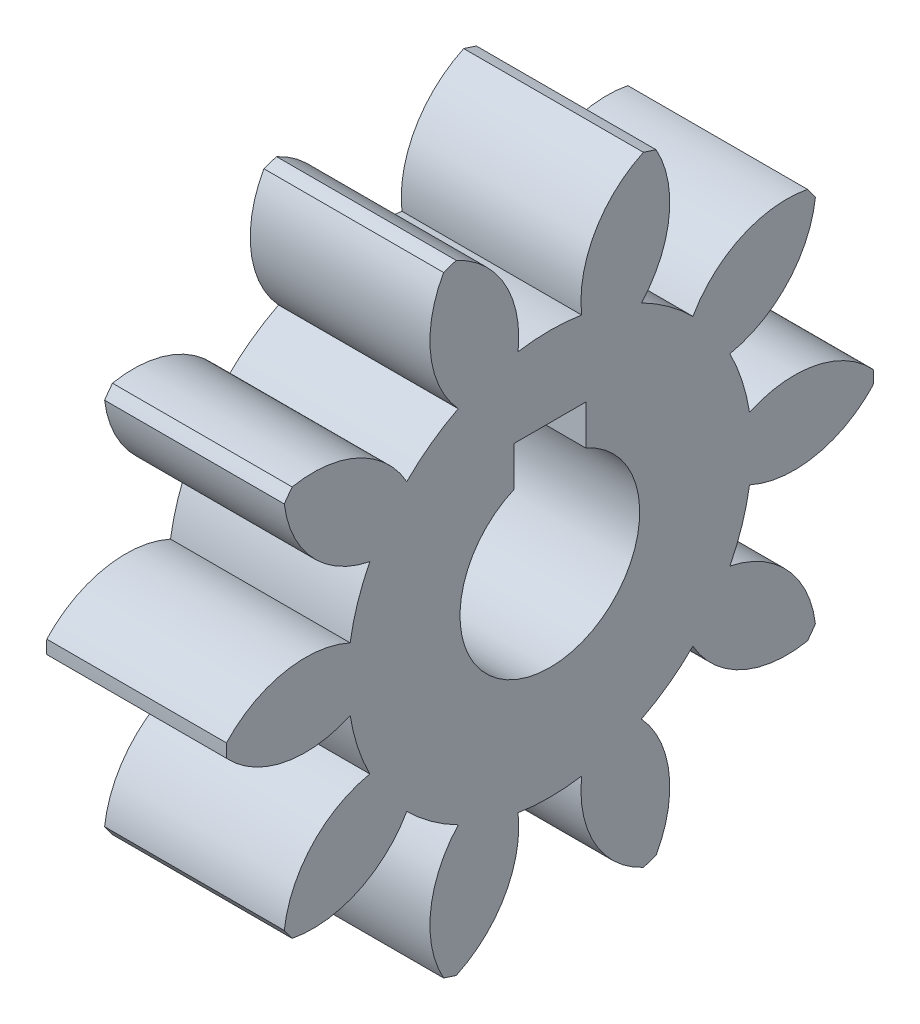
SolidWorks part; units mm, degrees
ref_plane "Plane1" through (0, 0, 0) normal (0, 0, 1) x (1, 0, 0)
ref_plane "Plane2" through (0, 0, 0) normal (0, 1, 0) x (1, 0, 0)
ref_plane "Plane3" through (0, 0, 0) normal (1, 0, 0) x (0, 0, -1)
sketch "HoldingSke" plane through (0, 0, 0) normal (0, 1, 0) x (1, 0, 0)
  line L0 (0, 0) -> (0.3283, -0.0579)
  line L1 (-15, 0) -> (100, 0) construction
  line L2 (0, 0) -> (-2.1039, 2.3779)
  line L3 (0, 0) -> (-11.863, 4.5341)
  line L4 (0, 0) -> (8.5048, 1.4996)
  line L5 (0, 0) -> (-46.8476, -17.4728)
  line L6 (0, 0) -> (-8.2896, -5.593)
  line L7 (-2.1039, 2.3779) -> (8.6586, 51.2059)
  line L8 (-76.2, 54.61) -> (-74.4, 54.61)
  line L9 (-71.009, 38.7566) -> (-53.1078, 45.2721)
  line L10 (-76.2, 71.12) -> (104.1128, 71.12)
  line L11 (0, 0) -> (-10, 0)
  line L12 (-76.2, 101.6) -> (-76.093, 101.6)
  line L13 (24.9733, 27.94) -> (52.9518, 28.4284)
  line L14 (24.9733, 27.94) -> (24.9743, 27.94)
  line L15 (24.9733, 27.94) -> (100.4006, 29.5858)
  line L16 (-63.627, -3) -> (-12.827, -3)
  circle A0 centre (0, 0) radius 5
  circle A1 centre (0, 0) radius 11.249
  circle A2 centre (0, 0) radius 37.5
  circle A3 centre (0, 0) radius 5
  dimension "MHD" = 22.498
  dimension "Hub_dia" = 75
  dimension "Bore" = 10
  dimension "MBD" = 10
  dimension "Num_teeth" = 10
  dimension "Pitch" = 0.3333
  dimension "Overall_len" = 50
  dimension "Show_teeth" = 10
  dimension "Thickness" = 10
  dimension "OAL" = 50.0001
  dimension "T_dim" = 1.8
  dimension "Ap" = 20
  dimension "H" = 19.05
  dimension "Pitch_radius" = 180.3128
  dimension "Width" = 10
  dimension "Backlash" = 0.107
  dimension "Addendum_fac" = 1
  dimension "Dedendum_fac" = 1.25
  dimension "Clearance_fac" = 0.25
  dimension "Dedendum_add" = 0.001
  dimension "Module" = 3
sketch "BasProSke" plane through (0, 0, 0) normal (0, 1, 0) x (1, 0, 0)
  line L0 (-10, 0) -> (60, 0) construction
  line L1 (0, 0) -> (0, 18)
  line L2 (0, 0) -> (10, 0)
  line L3 (10, 0) -> (10, 18)
  line L4 (10, 18) -> (0, 18)
  dimension "Thickness" = 10
  dimension "Diameter" = 36
revolve "Base-Revolve" add sketch "BasProSke" angle 360 about L0
sketch "TooCutSke" plane through (0, 0, 0) normal (1, 0, 0) x (0, 0, -1)
  line L1 (0, 0) -> (0, 107) construction
  line L2 (0, 0) -> (-2.5334, 14.7845) construction
  line L3 (0, 0) -> (-9.174, 28.2345) construction
  line L4 (-2.5334, 14.7845) -> (-4.587, 14.1173) construction
  arc A0 (1.7689, 11.109) -> (-1.7689, 11.109) centre (0, 0) ccw
  arc A1 (5.2426, 17.2462) -> (-5.2426, 17.2462) centre (0, 0) ccw
  circle A2 centre (0, 0) radius 15 construction
  circle A3 centre (0, 0) radius 14.0954 construction
  arc A4 (-1.7689, 11.109) -> (-5.2426, 17.2462) centre (-7.7306, 11.7863) ccw
  arc A5 (5.2426, 17.2462) -> (1.7689, 11.109) centre (7.7306, 11.7863) ccw
  dimension "Root_dia" = 22.498
  dimension "Overcut_dia" = 36.0508
  dimension "Pitch_dia" = 30
  dimension "Base_dia" = 28.1908
  dimension "Flank_rad" = 6
  dimension "Half_ang" = 18
  dimension "Half_CT" = 2.1593
extrude "ToothCut" cut sketch "TooCutSke" along normal through all
fillet "Breaks" [suppressed] radius 0.06
fillet "RootFillets" [suppressed] radius 0.751
pattern_circular "TeethCuts" count 10 every 36 about axis through (-10, 0, 0) along (1, 0, 0) of "ToothCut", "RootFillets", "Breaks"
sketch "HubNeaOneSke" plane through (0, 0, 0) normal (-1, 0, 0) x (0, 0, 1)
  circle A0 centre (0, 0) radius 11.249
  dimension "Diameter" = 22.498
extrude "HubNearOne" [suppressed] add sketch "HubNeaOneSke" along normal blind 40.0001
sketch "HubNeaBotSke" plane through (0, 0, 0) normal (-1, 0, 0) x (0, 0, 1)
  circle A0 centre (0, 0) radius 11.249
  dimension "Diameter" = 22.498
extrude "HubNearBoth" [suppressed] add sketch "HubNeaBotSke" along normal blind 20
ref_plane "FarPln" through (10, 0, 0) normal (1, 0, 0) x (0, 0, -1)
sketch "HubFarSke" plane through (10, 0, 0) normal (1, 0, 0) x (0, 0, -1)
  circle A0 centre (0, 0) radius 11.249
  dimension "Diameter" = 22.498
extrude "HubFar" [suppressed] add sketch "HubFarSke" along normal blind 20
sketch "BorSke" plane through (0, 0, 0) normal (1, 0, 0) x (0, 0, -1)
  circle A0 centre (0, 0) radius 5
  dimension "Diameter" = 10
extrude "Bore" cut sketch "BorSke" along normal mid plane 100.0001
sketch "KeySke" plane through (0, 0, 0) normal (1, 0, 0) x (0, 0, -1)
  line L0 (-2, 0) -> (-2, 6.8)
  line L1 (-2, 6.8) -> (2, 6.8)
  line L2 (2, 6.8) -> (2, 0)
  line L3 (0, 0) -> (0, 34) construction
  line L4 (-2, 0) -> (2, 0)
  dimension "Offset" = 6.8
  dimension "Width" = 4
extrude "Keyway" cut sketch "KeySke" along normal mid plane 100.0001
pattern_circular "Keyway2" [suppressed] count 2 every 90 about axis through (-10, 0, 0) along (1, 0, 0)
equation "' \"Module@HoldingSke\" = 6.35"
equation "' \"Num_teeth@HoldingSke\" = 12"
equation "' \"Ap@HoldingSke\" =  20"
equation "' \"Ap@HoldingSke\" = 20"
equation "' \"Width@HoldingSke\" = 0.5 * 25.4"
equation "' \"Hub_dia@HoldingSke\"= 1 * 25.4"
equation "' \"Hub_dia@HoldingSke\" = 1 * 25.4"
equation "' \"Overall_len@HoldingSke\" = 1.0 * 25.4"
equation "' \"Bore@HoldingSke\" = 0.75 * 25.4"
equation "' \"T_dim@HoldingSke\" = 0.1 * 25.4"
equation "' \"Width@KeySke\" = 0.25 * 25.4"
equation "' \"Show_teeth@HoldingSke\" = 13"
equation "' \"Backlash@HoldingSke\" = 0.009 * 25.4"
equation "' \"Addendum_fac@HoldingSke\" = 1.0"
equation "' \"Dedendum_fac@HoldingSke\" = 1.25"
equation "' \"Dedendum_add@HoldingSke\" = 0.00005 * 25.4"
equation "' \"Clearance_fac@HoldingSke\" = 0.25"
equation "\"Pitch@HoldingSke\" = 1 / \"Module@HoldingSke\""
equation "\"Overcut_dia@TooCutSke\" = (\"Num_teeth@HoldingSke\" + 2 * \"Addendum_fac@HoldingSke\") / \"Pitch@HoldingSke\" + 0.002 * 25.4"
equation "\"Pitch_dia@TooCutSke\" = \"Num_teeth@HoldingSke\" / \"Pitch@HoldingSke\""
equation "\"Base_dia@TooCutSke\" = \"Num_teeth@HoldingSke\" / \"Pitch@HoldingSke\" * cos((\"Ap@HoldingSke\"  * 3.14159265 / 180))"
equation "\"Root_dia@TooCutSke\" = (\"Num_teeth@HoldingSke\" + 2) / \"Pitch@HoldingSke\" - 2 * (\"Addendum_fac@HoldingSke\" + \"Dedendum_fac@HoldingSke\") / \"Pitch@HoldingSke\" - \"Dedendum_add@HoldingSke\" * 2"
equation "\"Half_ang@TooCutSke\" = 180 / \"Num_teeth@HoldingSke\""
equation "\"Half_CT@TooCutSke\" = \"Num_teeth@HoldingSke\" / \"Pitch@HoldingSke\" * sin((3.14159265 / 2 / \"Num_teeth@HoldingSke\")) / 2 - 7 * \"Backlash@HoldingSke\" / 4"
equation "\"Flank_rad@TooCutSke\" = \"Num_teeth@HoldingSke\" / \"Pitch@HoldingSke\" / 5"
equation "\"Radius@RootFillets\" = \"Clearance_fac@HoldingSke\" / \"Pitch@HoldingSke\" + \"Dedendum_add@HoldingSke\""
equation "\"Break_rad@Breaks\" = 0.02 / \"Pitch@HoldingSke\""
equation "\"Thickness@HoldingSke\" = \"Width@HoldingSke\""
equation "\"OAL@HoldingSke\" = \"Thickness@HoldingSke\""
equation "\"MHD@HoldingSke\" = (\"Num_teeth@HoldingSke\" + 2) / \"Pitch@HoldingSke\" - 2 * (\"Addendum_fac@HoldingSke\" + \"Dedendum_fac@HoldingSke\")  / \"Pitch@HoldingSke\" - \"Dedendum_add@HoldingSke\" * 2"
equation "\"MBD@HoldingSke\" = (\"Num_teeth@HoldingSke\" + 2) / \"Pitch@HoldingSke\" - 2 * (\"Addendum_fac@HoldingSke\" + \"Dedendum_fac@HoldingSke\")  / \"Pitch@HoldingSke\" - \"Dedendum_add@HoldingSke\" * 2 - 0.002 * 25.4"
equation "\"MHD@HoldingSke\" = ((sgn( \"MHD@HoldingSke\" - \"Hub_dia@HoldingSke\" )-1)*( \"MHD@HoldingSke\" - \"Hub_dia@HoldingSke\" ))/-2+ \"Hub_dia@HoldingSke\""
equation "\"MBD@HoldingSke\" = ((sgn( \"MBD@HoldingSke\" - \"Bore@HoldingSke\" )-1)*( \"MBD@HoldingSke\" - \"Bore@HoldingSke\" ))/-2+ \"Bore@HoldingSke\""
equation "\"OAL@HoldingSke\" = ((sgn( \"OAL@HoldingSke\" - \"Overall_len@HoldingSke\" )+1)*( \"OAL@HoldingSke\" - \"Overall_len@HoldingSke\" ))/2 + \"Overall_len@HoldingSke\" + 0.000002 * 25.4"
equation "\"Num_teeth@TeethCuts\" = int( \"Show_teeth@HoldingSke\" ) + 1"
equation "\"Num_teeth@TeethCuts\" = ((sgn( \"Num_teeth@TeethCuts\" - \"Num_teeth@HoldingSke\" )-1)*( \"Num_teeth@TeethCuts\" - \"Num_teeth@HoldingSke\" ))/-2+ \"Num_teeth@HoldingSke\""
equation "\"Num_teeth@TeethCuts\" = ((sgn( \"Num_teeth@TeethCuts\" - 2.0)+1)*( \"Num_teeth@TeethCuts\" - 2.0))/2 +2.0"
equation "\"Angle@TeethCuts\" = 360.0 / \"Num_teeth@HoldingSke\""
equation "\"Diameter@BasProSke\" = (\"Num_teeth@HoldingSke\" + 2 * \"Addendum_fac@HoldingSke\") / \"Pitch@HoldingSke\""
equation "\"Thickness@BasProSke\"  = \"Thickness@HoldingSke\""
equation "' \"Fillet_rad@BasProSke\" =  \"Thickness@HoldingSke\" * 0.05"
equation "' \"Fillet_rad@BasProSke\" = \"Thickness@HoldingSke\" * 0.05"
equation "\"MHD@HoldingSke\" = ((sgn( \"MHD@HoldingSke\" - \"Root_dia@TooCutSke\" )-1)*( \"MHD@HoldingSke\" - \"Root_dia@TooCutSke\" ))/-2+ \"Root_dia@TooCutSke\""
equation "\"Diameter@HubNeaOneSke\" = \"MHD@HoldingSke\""
equation "\"Length@HubNearOne\" = \"OAL@HoldingSke\" - \"Thickness@BasProSke\""
equation "\"Diameter@HubNeaBotSke\" = \"MHD@HoldingSke\""
equation "\"Length@HubNearBoth\" = ( \"OAL@HoldingSke\" - \"Thickness@BasProSke\" ) / 2.0"
equation "\"Thickness@FarPln\" = \"Thickness@BasProSke\""
equation "\"Diameter@HubFarSke\" = \"MHD@HoldingSke\""
equation "\"Length@HubFar\" = ( \"OAL@HoldingSke\" - \"Thickness@BasProSke\" ) / 2.0"
equation "\"Diameter@BorSke\" = \"MBD@HoldingSke\""
equation "\"D1@Bore\" = \"OAL@HoldingSke\" * 2.0"
equation "\"D1@Keyway\" = \"OAL@HoldingSke\" * 2.0"
equation "\"Offset@KeySke\" = \"T_dim@HoldingSke\" + \"MBD@HoldingSke\" / 2.0"
